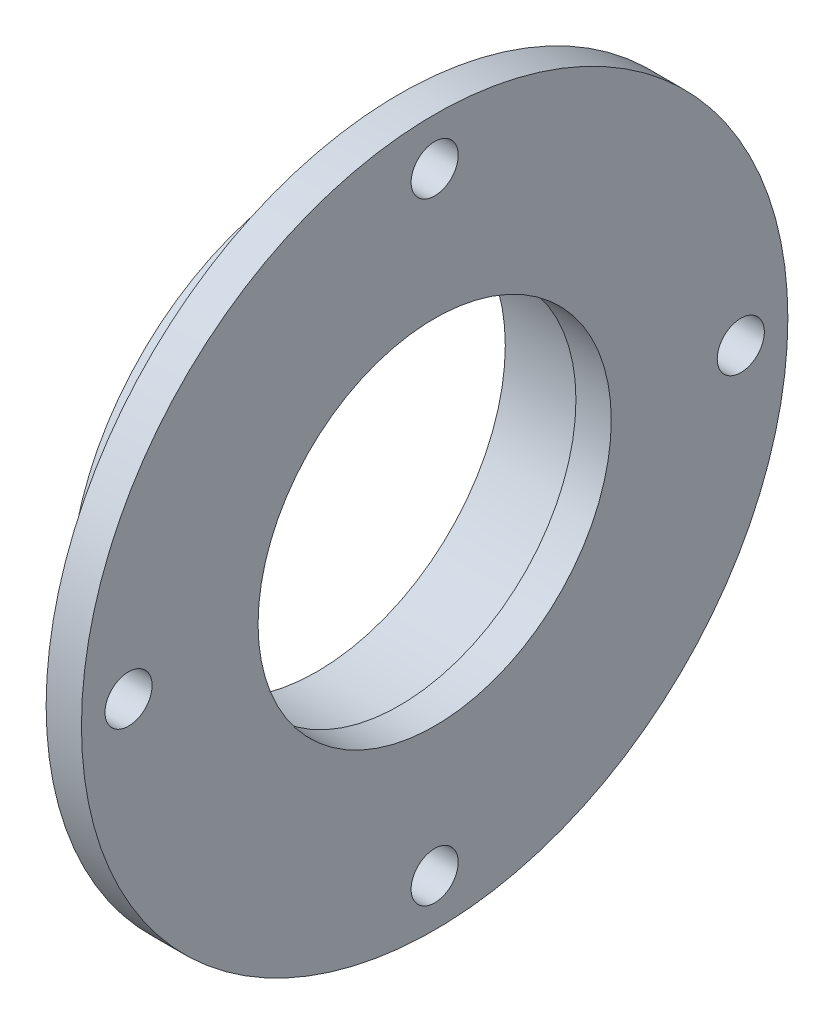
SolidWorks part; units mm, degrees
material "2024-T4"
ref_plane "Front Plane" through (0, 0, 0) normal (0, 0, 1) x (1, 0, 0)
ref_plane "Top Plane" through (0, 0, 0) normal (0, 1, 0) x (1, 0, 0)
ref_plane "Right Plane" through (0, 0, 0) normal (1, 0, 0) x (0, 0, -1)
sketch "Sketch1" plane through (0, 0, 0) normal (1, 0, 0) x (0, 0, -1)
  circle A0 centre (0, 0) radius 21
  dimension "D1" = 42
extrude "Boss-Extrude1" add sketch "Sketch1" along normal blind 7
sketch "Sketch2" plane through (7, 0, 0) normal (1, 0, 0) x (0, 0, -1)
  circle A0 centre (0, 0) radius 30
  dimension "D1" = 60
extrude "Boss-Extrude2" add sketch "Sketch2" along normal blind 3
sketch "Sketch3" plane through (0, 0, 0) normal (-1, 0, 0) x (0, 0, 1)
  circle A0 centre (0, 0) radius 16
  dimension "D1" = 32
extrude "Cut-Extrude1" cut sketch "Sketch3" against normal through all
sketch "Sketch4" plane through (0, 0, 0) normal (-1, 0, 0) x (0, 0, 1)
  circle A0 centre (0, 18.5) radius 1.5
  circle A1 centre (0, 0) radius 18.5 construction
  circle A2 centre (18.5, 0) radius 1.5
  circle A3 centre (0, -18.5) radius 1.5
  circle A4 centre (-18.5, 0) radius 1.5
  point P13 (0, 0)
  dimension "D1" = 3
  dimension "D2" = 37
  dimension "D3" = 4
extrude "Cut-Extrude2" cut sketch "Sketch4" against normal blind 5
sketch "Sketch5" plane through (10, 0, 0) normal (1, 0, 0) x (0, 0, -1)
  circle A0 centre (0, 0) radius 15
  circle A1 centre (0, 0) radius 16 construction
  circle A2 centre (0, 0) radius 16
  dimension "D1" = 30
extrude "Boss-Extrude3" add sketch "Sketch5" against normal blind 3
sketch "Sketch6" plane through (7, 0, 0) normal (-1, 0, 0) x (0, 0, 1)
  circle A0 centre (0, 0) radius 26 construction
  circle A1 centre (0, 26) radius 2
  circle A2 centre (26, 0) radius 2
  circle A3 centre (0, -26) radius 2
  circle A4 centre (-26, 0) radius 2
  point P14 (0, 0)
  dimension "D1" = 52
  dimension "D2" = 4
  dimension "D3" = 4
extrude "Cut-Extrude3" cut sketch "Sketch6" against normal through all
sketch "Sketch8" [suppressed] plane through (0, 0, 0) normal (1, 0, 0) x (0, 0, -1)
  circle A0 centre (0, 0) radius 21
  circle A1 centre (0, 0) radius 16
  dimension "D1" = 32
  dimension "D2" = 42
extrude "Boss-Extrude4" [suppressed] add sketch "Sketch8" along normal blind 7
sketch "Sketch9" [suppressed] plane through (0, 0, 0) normal (-1, 0, 0) x (0, 0, 1)
  circle A1 centre (0, 0) radius 21 construction
  circle A2 centre (0, 0) radius 21
  circle A3 centre (0, 0) radius 15
  dimension "D1" = 30
extrude "Boss-Extrude5" [suppressed] add sketch "Sketch9" along normal blind 3
sketch "Sketch10" [suppressed] plane through (7, 0, 0) normal (1, 0, 0) x (0, 0, -1)
  circle A0 centre (0, 0) radius 16 construction
  circle A1 centre (0, 0) radius 16
  circle A3 centre (0, 0) radius 30
  dimension "D1" = 60
extrude "Boss-Extrude6" [suppressed] add sketch "Sketch10" along normal blind 3
sketch "Sketch11" [suppressed] plane through (10, 0, 0) normal (1, 0, 0) x (0, 0, -1)
  circle A0 centre (0, 0) radius 18.5 construction
  circle A1 centre (0, 0) radius 26 construction
  circle A2 centre (0, 18.5) radius 1.5
  circle A3 centre (0, 26) radius 2
  circle A4 centre (26, 0) radius 2
  circle A5 centre (18.5, 0) radius 1.5
  circle A6 centre (0, -26) radius 2
  circle A7 centre (0, -18.5) radius 1.5
  circle A8 centre (-26, 0) radius 2
  circle A9 centre (-18.5, 0) radius 1.5
  point P22 (0, 0)
  dimension "D1" = 3
  dimension "D2" = 4
  dimension "D3" = 37
  dimension "D4" = 52
  dimension "D5" = 4
extrude "Cut-Extrude4" [suppressed] cut sketch "Sketch11" against normal blind 6
